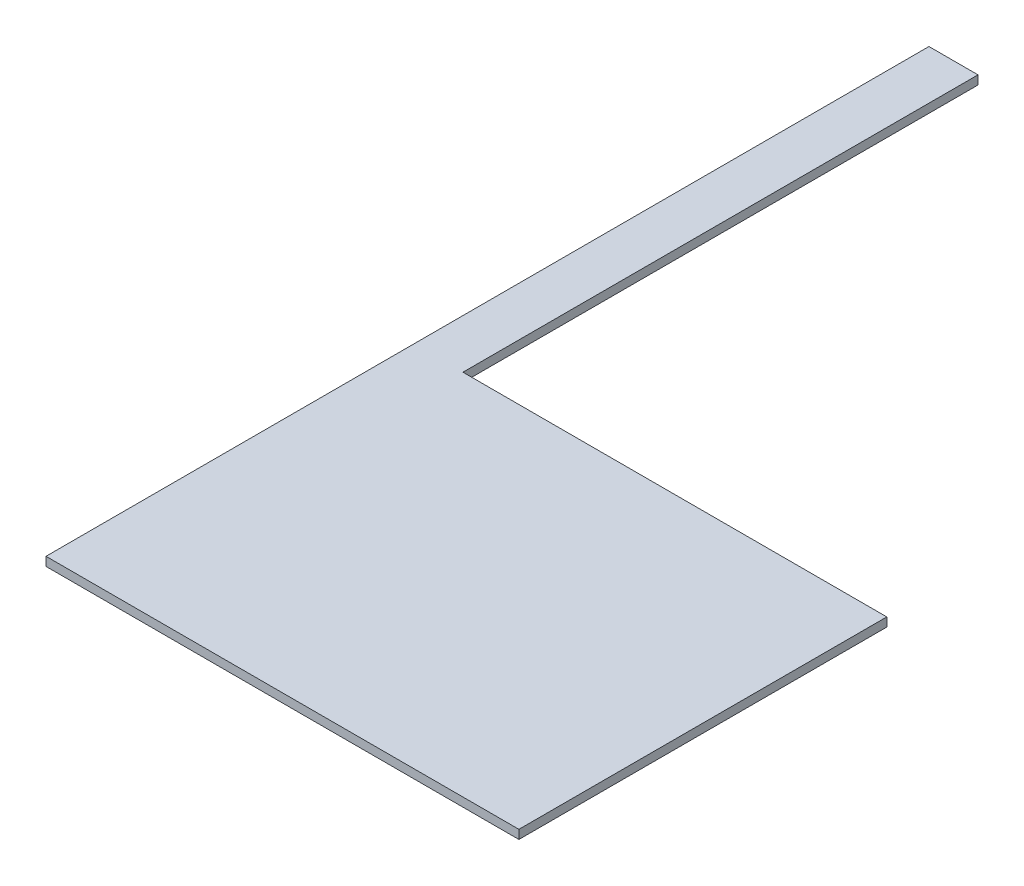
SolidWorks part; units mm, degrees
ref_plane "Front Plane" through (0, 0, 0) normal (0, 0, 1) x (1, 0, 0)
ref_plane "Top Plane" through (0, 0, 0) normal (0, 1, 0) x (1, 0, 0)
ref_plane "Right Plane" through (0, 0, 0) normal (1, 0, 0) x (0, 0, -1)
sketch "Sketch1" plane through (0, 0, 0) normal (0, 1, 0) x (1, 0, 0)
  line L0 (-489.7438, 381) -> (-489.7438, 1447.8)
  line L1 (-489.7438, -381) -> (489.7437, -381)
  line L2 (-489.7438, -381) -> (-489.7438, 381)
  line L4 (489.7437, -381) -> (489.7437, 381)
  line L5 (-489.7438, -381) -> (489.7437, 381) construction
  line L6 (-489.7438, 381) -> (489.7437, -381) construction
  line L7 (-489.7438, 1447.8) -> (-388.1438, 1447.8)
  line L8 (-388.1438, 1447.8) -> (-388.1438, 381)
  line L9 (489.7437, 381) -> (-388.1438, 381)
  point P0 (0, 0)
  dimension "D1" = 762
  dimension "D2" = 979.4875
  dimension "D3" = 101.6
  dimension "D4" = 1066.8
extrude "Boss-Extrude1" add sketch "Sketch1" along normal blind 18.2562
